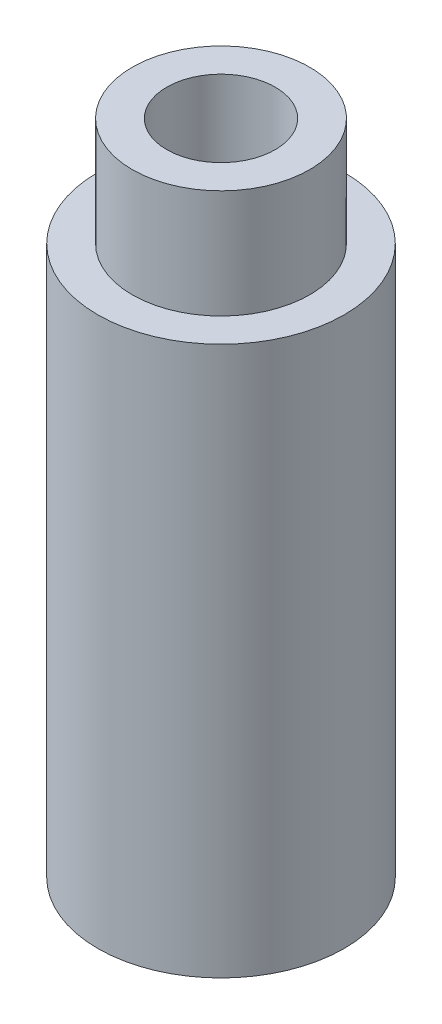
SolidWorks part; units mm, degrees
ref_plane "Front Plane" through (0, 0, 0) normal (0, 0, 1) x (1, 0, 0)
ref_plane "Top Plane" through (0, 0, 0) normal (0, 1, 0) x (1, 0, 0)
ref_plane "Right Plane" through (0, 0, 0) normal (1, 0, 0) x (0, 0, -1)
sketch "Sketch1" plane through (0, 0, 0) normal (0, 1, 0) x (1, 0, 0)
  circle A0 centre (0, 0) radius 3.3
  circle A1 centre (0, 0) radius 5.4
  dimension "D1" = 6.6
  dimension "D2" = 10.8
extrude "Boss-Extrude1" add sketch "Sketch1" along normal blind 40
sketch "Sketch2" plane through (0, 40, 0) normal (0, 1, 0) x (1, 0, 0)
  circle A0 centre (0, 0) radius 7.5
  circle A1 centre (0, 0) radius 3.3
  dimension "D1" = 15
extrude "Boss-Extrude2" add sketch "Sketch2" against normal up to surface (33.4 mm away) from offset 6.6 up to face at (0, 0, 5.4)
